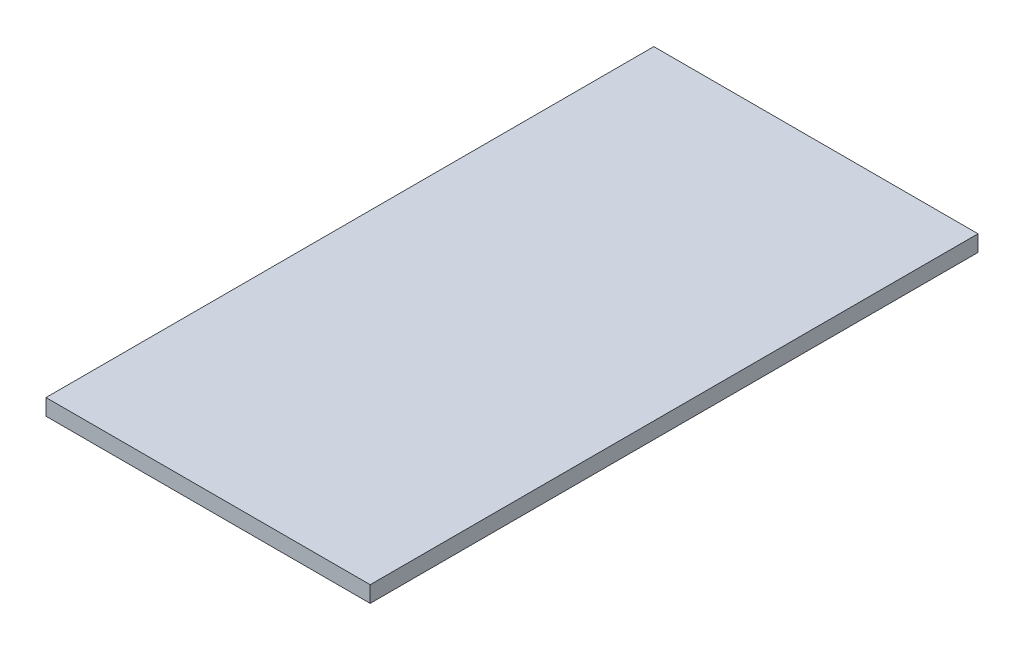
SolidWorks part; units mm, degrees
ref_plane "Front Plane" through (0, 0, 0) normal (0, 0, 1) x (1, 0, 0)
ref_plane "Top Plane" through (0, 0, 0) normal (0, 1, 0) x (1, 0, 0)
ref_plane "Right Plane" through (0, 0, 0) normal (1, 0, 0) x (0, 0, -1)
sketch "Sketch1" plane through (0, 0, 0) normal (0, 1, 0) x (1, 0, 0)
  line L2 (-40, 75) -> (40, 75)
  line L3 (-40, 75) -> (-40, -75)
  line L4 (-40, -75) -> (40, -75)
  line L5 (40, 75) -> (40, -75)
  line L6 (-40, 75) -> (40, -75) construction
  line L7 (-40, -75) -> (40, 75) construction
  point P2 (0, 0)
  dimension "D1" = 80
  dimension "D2" = 150
extrude "Boss-Extrude1" add sketch "Sketch1" along normal blind 4
